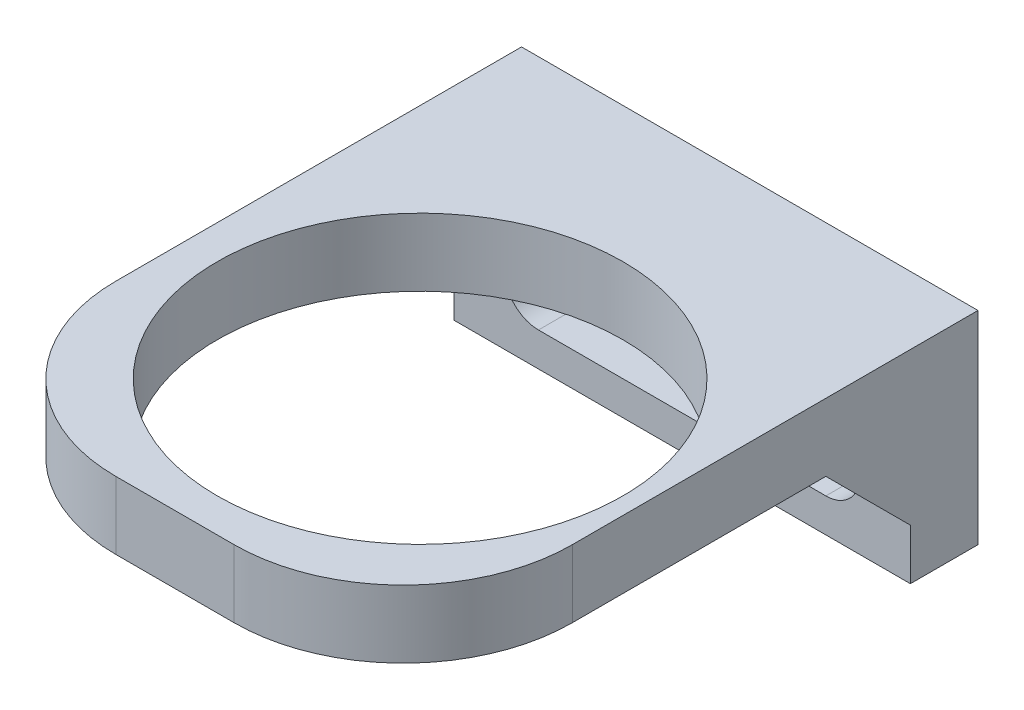
SolidWorks part; units mm, degrees
ref_plane "Plan de face" through (0, 0, 0) normal (0, 0, 1) x (1, 0, 0)
ref_plane "Plan de dessus" through (0, 0, 0) normal (0, 1, 0) x (1, 0, 0)
ref_plane "Plan de droite" through (0, 0, 0) normal (1, 0, 0) x (0, 0, -1)
sketch "Esquisse1" plane through (0, 0, 0) normal (0, 1, 0) x (1, 0, 0)
  line L1 (-14, 20) -> (13, 20)
  line L2 (-14, 20) -> (-14, -14)
  line L3 (-14, -14) -> (13, -14)
  line L4 (13, 20) -> (13, -14)
  line L6 (-14, 0) -> (13, 0) construction
  circle A0 centre (0, 0) radius 12
  dimension "D1" = 24
  dimension "D2" = 27
  dimension "D3" = 34
  dimension "D4" = 14
  dimension "D5" = 13
extrude "Boss.-Extru.1" add sketch "Esquisse1" along normal blind 4
sketch "Esquisse2" plane through (0, 0, 0) normal (0, -1, 0) x (1, 0, 0)
  line L0 (13, 14) -> (13, -20) construction
  line L1 (-14, -20) -> (13, -20)
  line L2 (-14, -20) -> (-14, -16)
  line L3 (-14, -16) -> (13, -16)
  line L4 (13, -20) -> (13, -16)
  dimension "D1" = 4
extrude "Boss.-Extru.2" add sketch "Esquisse2" along normal blind 8
sketch "Esquisse5" plane through (-14, 0, 0) normal (-1, 0, 0) x (0, 0, 1)
  line L0 (-16, 0) -> (-16, -5)
  line L1 (-16, -8) -> (-16, 0) construction
  line L2 (-16, -5) -> (-11, 0)
  line L3 (-16, 0) -> (14, 0) construction
  line L4 (-11, 0) -> (-16, 0)
  dimension "D1" = 45
  dimension "D2" = 5
extrude "Boss.-Extru.3" add sketch "Esquisse5" against normal blind 2
sketch "Esquisse6" plane through (13, 0, 0) normal (1, 0, 0) x (0, 0, -1)
  line L0 (16, 0) -> (11, 0)
  line L1 (-14, 0) -> (16, 0) construction
  line L2 (11, 0) -> (16, -5)
  line L3 (16, -8) -> (16, 0) construction
  line L4 (16, -5) -> (16, 0)
  dimension "D1" = 45
  dimension "D2" = 5
extrude "Boss.-Extru.4" add sketch "Esquisse6" against normal blind 2
fillet "Congé1" radius 10 2 edges at (-14, 2, 14) (13, 2, 14)
sketch "Esquisse7" plane through (0, 0, -16) normal (0, 0, 1) x (1, 0, 0)
  line L0 (-9, -4) -> (8, -4) construction
  line L1 (-9, -2) -> (8, -2)
  line L2 (-9, -6) -> (8, -6)
  line L3 (13, -8) -> (13, -5) construction
  line L4 (-14, -8) -> (-14, -5) construction
  line L5 (11, 0) -> (-12, 0) construction
  arc A0 (-9, -2) -> (-9, -6) centre (-9, -4) ccw
  arc A1 (8, -6) -> (8, -2) centre (8, -4) ccw
  point P2 (-0.5, -4)
  dimension "D1" = 4
  dimension "D2" = 5
  dimension "D3" = 5
  dimension "D4" = 4
extrude "Enlèv. mat.-Extru.1" cut sketch "Esquisse7" against normal through all
